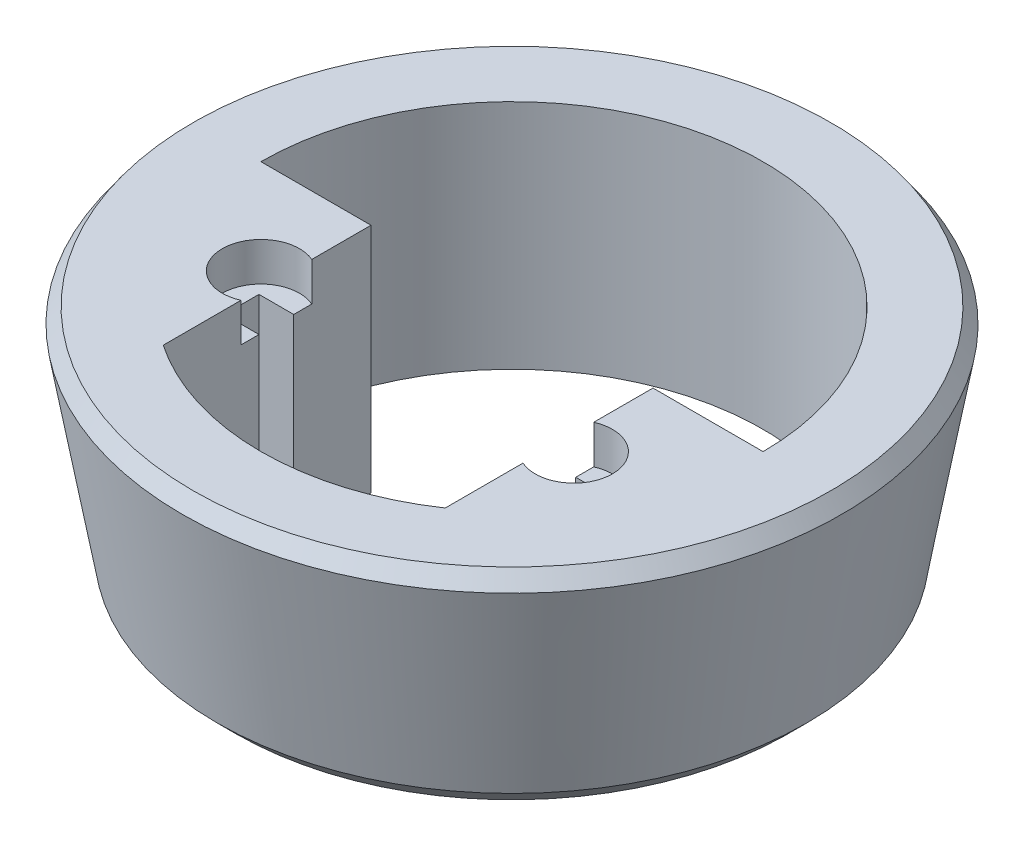
SolidWorks part; units mm, degrees
ref_plane "Front Plane" through (0, 0, 0) normal (0, 0, 1) x (1, 0, 0)
ref_plane "Top Plane" through (0, 0, 0) normal (0, 1, 0) x (1, 0, 0)
ref_plane "Right Plane" through (0, 0, 0) normal (1, 0, 0) x (0, 0, -1)
sketch "Sketch1" plane through (0, 0, 0) normal (0, 0, 1) x (1, 0, 0)
  line L0 (0, 0) -> (0, -15.8583) construction
  line L1 (0, 0) -> (-17.2, 0)
  line L2 (-17.2, 0) -> (-15.1, -12)
  line L3 (-15.1, -12) -> (0, -12)
  line L4 (0, 0) -> (0, -12)
  dimension "D1" = 34.4
  dimension "D2" = 30.2
  dimension "D3" = 12
revolve "Revolve1" add sketch "Sketch1" angle 360 about L0
sketch "Sketch2" plane through (0, 0, 0) normal (0, 1, 0) x (1, 0, 0)
  line L0 (0, 0) -> (0, -13.7261) construction
  line L1 (-9.1, -5.8) -> (-7.3, -5.8)
  line L2 (-9.1, -5.8) -> (-9.1, -4)
  line L3 (-9.1, -4) -> (-7.3, -4)
  line L4 (9.1, -5.8) -> (9.1, -4)
  line L5 (-7.3, -5.8) -> (-7.3, -10.7569)
  line L6 (-7.3, -4) -> (-7.3, 0)
  line L7 (-7.3, 0) -> (-13, 0)
  line L8 (7.3, 0) -> (13, 0)
  line L9 (7.3, -4) -> (7.3, 0)
  line L10 (7.3, -5.8) -> (7.3, -10.7569)
  line L11 (7.3, -5.8) -> (9.1, -5.8)
  line L12 (7.3, -4) -> (9.1, -4)
  arc A0 (13, 0) -> (-13, 0) centre (0, 0) ccw
  arc A1 (-7.3, -10.7569) -> (7.3, -10.7569) centre (0, 0) ccw
  dimension "D5" = 26
  dimension "D1" = 4
  dimension "D2" = 18.2
  dimension "D3" = 1.8
  dimension "D4" = 18.2
  dimension "D6" = 1.8
extrude "Cut-Extrude1" cut sketch "Sketch2" against normal through all
sketch "Sketch3" plane through (0, 0, 0) normal (0, 1, 0) x (1, 0, 0)
  line L1 (-7.3, -4) -> (-9.1, -4) construction
  line L2 (-7.3, 0) -> (-7.3, -4) construction
  line L3 (0, 0) -> (0, -9.4106) construction
  circle A0 centre (-8.1, -4.9) radius 2
  circle A1 centre (8.1, -4.9) radius 2
  dimension "D1" = 4
  dimension "D2" = 0.9
  dimension "D3" = 0.8
extrude "Cut-Extrude2" cut sketch "Sketch3" against normal blind 2
chamfer "Chamfer1" distance 0.8 angle 45 2 edges at (0, -12, 15.1) (0, 0, 17.2)
